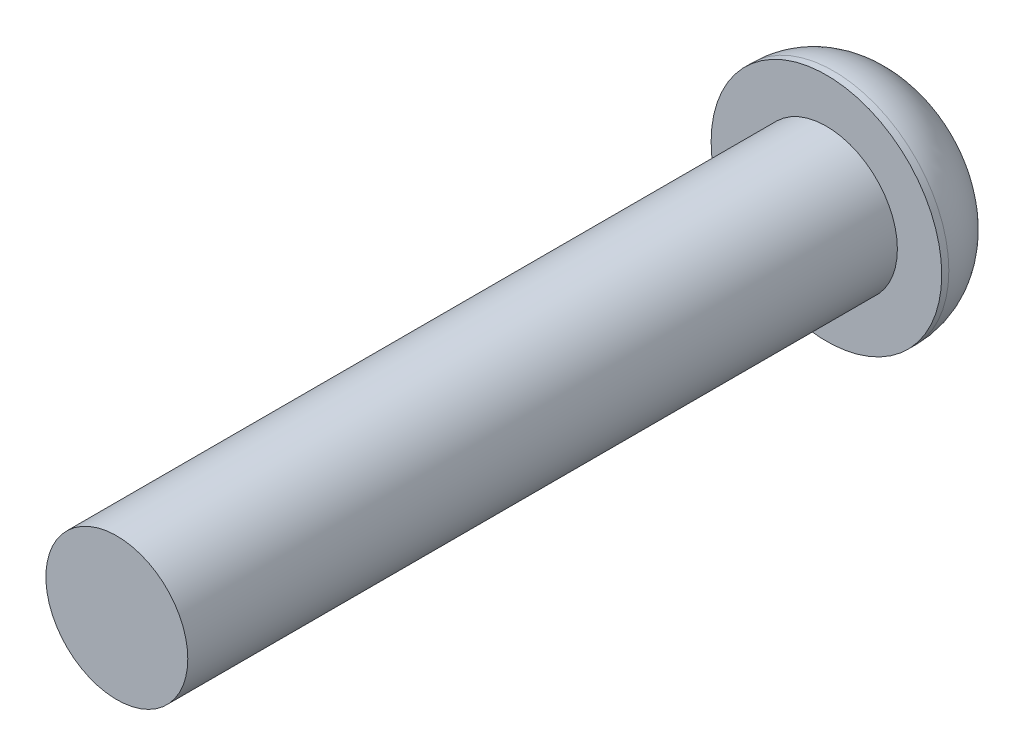
SolidWorks part; units mm, degrees
ref_plane "前视基准面" through (0, 0, 0) normal (0, 0, 1) x (1, 0, 0)
ref_plane "上视基准面" through (0, 0, 0) normal (0, 1, 0) x (1, 0, 0)
ref_plane "右视基准面" through (0, 0, 0) normal (1, 0, 0) x (0, 0, -1)
sketch "草图1" plane through (0, 0, 0) normal (0, 0, 1) x (1, 0, 0)
  circle A0 centre (0, 0) radius 2
  dimension "D1" = 4
extrude "凸台-拉伸1" add sketch "草图1" along normal blind 20
sketch "草图2" plane through (0, 0, 0) normal (0, 0, -1) x (-1, 0, 0)
  circle A0 centre (0, 0) radius 3.25
  dimension "D1" = 6.5
extrude "凸台-拉伸2" add sketch "草图2" along normal blind 2.2
fillet "圆角1" radius 2 1 edges at (-3.25, 0, -2.2)
sketch "草图3" plane through (0, 0, -2.2) normal (0, 0, -1) x (-1, 0, 0)
  line L0 (0, 3.24) -> (0, -3.24) construction
  line L1 (-3.24, 0) -> (3.24, 0) construction
  line L2 (-3.24, 0.25) -> (3.24, 0.25) construction
  line L3 (0.25, 3.24) -> (0.25, -3.24) construction
  line L4 (-3.24, -0.25) -> (3.24, -0.25) construction
  line L5 (-0.25, 3.24) -> (-0.25, -3.24) construction
  line L7 (3.24, 0.25) -> (3.24, -0.25)
  line L8 (-0.25, 3.24) -> (0.25, 3.24)
  line L10 (-0.25, 3.24) -> (-0.25, 0.25)
  line L11 (0.25, 3.24) -> (0.25, 0.25)
  line L12 (3.24, 0.25) -> (0.25, 0.25)
  line L13 (3.24, -0.25) -> (0.25, -0.25)
  line L15 (0.25, -3.24) -> (0.25, -0.25)
  line L16 (-0.25, -3.24) -> (-0.25, -0.25)
  line L17 (0.25, -3.24) -> (-0.25, -3.24)
  line L18 (-3.24, -0.25) -> (-0.25, -0.25)
  line L19 (-3.24, 0.25) -> (-0.25, 0.25)
  line L20 (-3.24, -0.25) -> (-3.24, 0.25)
  line L21 (3.24, 0.25) -> (3.24, -0.25) [skipped]
  circle A1 centre (0, 0) radius 3.24 construction
  dimension "D1" = 0.25
  dimension "D2" = 0.25
  dimension "D3" = 4
extrude "切除-拉伸1" cut sketch "草图3" against normal blind 0.5
